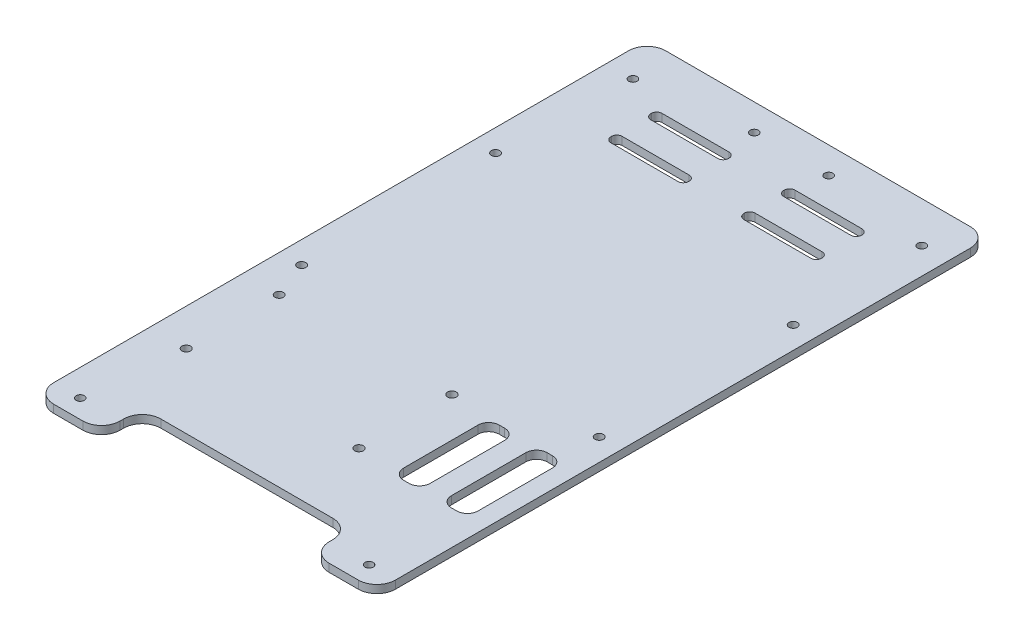
SolidWorks part; units mm, degrees
ref_plane "Front Plane" through (0, 0, 0) normal (0, 0, 1) x (1, 0, 0)
ref_plane "Top Plane" through (0, 0, 0) normal (0, 1, 0) x (1, 0, 0)
ref_plane "Right Plane" through (0, 0, 0) normal (1, 0, 0) x (0, 0, -1)
sketch "Sketch1" plane through (0, 0, 0) normal (0, 1, 0) x (1, 0, 0)
  line L1 (-90, 120) -> (90, 120)
  line L2 (-90, 120) -> (-90, -120)
  line L3 (-90, -120) -> (90, -120)
  line L4 (90, 120) -> (90, -120)
  line L5 (-90, 120) -> (90, -120) construction
  line L6 (-90, -120) -> (90, 120) construction
  point P0 (0, 0)
  dimension "D1" = 180
  dimension "D2" = 240
extrude "Boss-Extrude1" add sketch "Sketch1" along normal blind 3
sketch "Sketch3" plane through (0, 3, 0) normal (0, 1, 0) x (1, 0, 0)
  line L0 (0, 117.3388) -> (0, -121.3792) construction
  line L1 (90, 120) -> (-90, 120) construction
  circle A0 centre (14, 110) radius 1.55
  circle A1 centre (-14, 110) radius 1.55
  dimension "D1" = 3.1
  dimension "D2" = 14
  dimension "D3" = 10
extrude "Cut-Extrude2" cut sketch "Sketch3" against normal through all
sketch "Sketch4" plane through (0, 3, 0) normal (0, 1, 0) x (1, 0, 0)
  line L0 (-117.0852, 0) -> (125.1979, 0) construction
  line L1 (0, 106.2976) -> (0, -114.7172) construction
  line L2 (-2.6902, 10.0007) -> (-2.6902, -138.9813) construction
  circle A4 centre (-50.5, -32.2687) radius 1.6
  circle A5 centre (-50.5, -67.2687) radius 1.6
  circle A6 centre (14.5, -32.2687) radius 1.65
  circle A7 centre (14.5, -67.2687) radius 1.65
  dimension "D1" = 3.2
  dimension "D2" = 3.2
extrude "Cut-Extrude3" cut sketch "Sketch4" against normal through all
sketch "Sketch5" plane through (0, 3, 0) normal (0, 1, 0) x (1, 0, 0)
  line L0 (-125.4171, 0) -> (149.9743, 0) construction
  line L1 (0, -118.5902) -> (0, 143.2176) construction
  circle A0 centre (56, 54.6607) radius 1.6
  circle A1 centre (56, -18.3393) radius 1.6
  circle A2 centre (-56, -18.3393) radius 1.6
  circle A3 centre (-56, 54.6607) radius 1.6
  dimension "D1" = 3.2
  dimension "D2" = 3.2
  dimension "D3" = 3.2
  dimension "D4" = 3.2
extrude "Cut-Extrude4" cut sketch "Sketch5" against normal through all
sketch "Sketch6" plane through (0, 3, 0) normal (0, 1, 0) x (1, 0, 0)
  line L0 (-118.4996, 0) -> (129.5595, 0) construction
  line L1 (0, -107.1236) -> (0, 115.5797) construction
  circle A0 centre (-54.3214, -103.342) radius 1.55
  circle A1 centre (54.3786, -103.342) radius 1.55
  circle A2 centre (-54.3214, 104.658) radius 1.55
  circle A3 centre (54.3786, 104.658) radius 1.55
extrude "Cut-Extrude5" cut sketch "Sketch6" against normal through all
sketch "Sketch7" plane through (0, 3, 0) normal (0, 1, 0) x (1, 0, 0)
  line L0 (90, 120) -> (-90, 120) construction
  line L1 (37.63, 79.7011) -> (12.3993, 79.7011)
  line L2 (-37.63, 83.9122) -> (-12.3993, 83.9122)
  line L3 (-90, 120) -> (-64.3214, 120)
  line L4 (-90, 120) -> (-90, -120)
  line L5 (-90, -120) -> (-64.3214, -120)
  line L6 (-64.3214, 120) -> (-64.3214, -120)
  line L7 (-90, 120) -> (-90, -120) construction
  line L8 (-90, -120) -> (90, -120) construction
  line L9 (0, 130.596) -> (0, -150.1626) construction
  line L10 (-39.3214, -120) -> (39.3786, -120)
  line L11 (-39.3214, -120) -> (-39.3214, -95)
  line L12 (-39.3214, -95) -> (39.3786, -95)
  line L13 (39.3786, -120) -> (39.3786, -95)
  line L14 (90, -120) -> (64.3214, -120)
  line L15 (64.3214, 120) -> (64.3214, -120)
  line L16 (90, 120) -> (64.3214, 120)
  line L17 (90, 120) -> (90, -120)
  line L18 (29.3454, -37.3012) -> (29.3454, -65.3012)
  line L19 (51.3454, -33.3012) -> (53.3454, -33.3012)
  line L20 (47.3454, -37.3012) -> (47.3454, -65.3012)
  line L21 (51.3454, -69.3012) -> (53.3454, -69.3012)
  line L22 (57.3454, -37.3012) -> (57.3454, -65.3012)
  line L23 (33.3454, -33.3012) -> (35.3454, -33.3012)
  line L24 (39.3454, -37.3012) -> (39.3454, -65.3012)
  line L25 (33.3454, -69.3012) -> (35.3454, -69.3012)
  line L26 (37.63, 94.7011) -> (12.3993, 94.7011)
  line L27 (-37.63, 98.9122) -> (-12.3993, 98.9122)
  line L28 (-39.63, 96.9122) -> (-39.63, 96.7011)
  line L29 (-37.63, 94.7011) -> (-12.3993, 94.7011)
  line L30 (-10.3993, 96.9122) -> (-10.3993, 96.7011)
  line L31 (-39.63, 98.9122) -> (-10.3993, 94.7011) construction
  line L32 (-39.63, 94.7011) -> (-10.3993, 98.9122) construction
  line L33 (10.3993, 96.9122) -> (10.3993, 96.7011)
  line L34 (37.63, 98.9122) -> (12.3993, 98.9122)
  line L35 (39.63, 96.9122) -> (39.63, 96.7011)
  line L36 (-39.63, 81.9122) -> (-39.63, 81.7011)
  line L37 (-37.63, 79.7011) -> (-12.3993, 79.7011)
  line L38 (-10.3993, 81.9122) -> (-10.3993, 81.7011)
  line L39 (10.3993, 81.9122) -> (10.3993, 81.7011)
  line L40 (37.63, 83.9122) -> (12.3993, 83.9122)
  line L41 (39.63, 81.9122) -> (39.63, 81.7011)
  line L42 (-39.63, 83.9122) -> (-10.3993, 79.7011) construction
  line L43 (-39.63, 79.7011) -> (-10.3993, 83.9122) construction
  circle A0 centre (-54.3214, -103.342) radius 1.55 construction
  circle A1 centre (54.3786, -103.342) radius 1.55 construction
  arc A2 (51.3454, -69.3012) -> (47.3454, -65.3012) centre (51.3454, -65.3012) cw
  arc A3 (53.3454, -69.3012) -> (57.3454, -65.3012) centre (53.3454, -65.3012) ccw
  arc A4 (57.3454, -37.3012) -> (53.3454, -33.3012) centre (53.3454, -37.3012) ccw
  arc A5 (47.3454, -37.3012) -> (51.3454, -33.3012) centre (51.3454, -37.3012) cw
  arc A6 (35.3454, -69.3012) -> (39.3454, -65.3012) centre (35.3454, -65.3012) ccw
  arc A7 (33.3454, -69.3012) -> (29.3454, -65.3012) centre (33.3454, -65.3012) cw
  arc A8 (35.3454, -33.3012) -> (39.3454, -37.3012) centre (35.3454, -37.3012) cw
  arc A9 (29.3454, -37.3012) -> (33.3454, -33.3012) centre (33.3454, -37.3012) cw
  arc A10 (-37.63, 94.7011) -> (-39.63, 96.7011) centre (-37.63, 96.7011) cw
  arc A11 (-37.63, 98.9122) -> (-39.63, 96.9122) centre (-37.63, 96.9122) ccw
  arc A12 (-10.3993, 96.7011) -> (-12.3993, 94.7011) centre (-12.3993, 96.7011) cw
  arc A13 (-12.3993, 98.9122) -> (-10.3993, 96.9122) centre (-12.3993, 96.9122) cw
  arc A14 (10.3993, 96.7011) -> (12.3993, 94.7011) centre (12.3993, 96.7011) ccw
  arc A15 (12.3993, 98.9122) -> (10.3993, 96.9122) centre (12.3993, 96.9122) ccw
  arc A16 (37.63, 94.7011) -> (39.63, 96.7011) centre (37.63, 96.7011) ccw
  arc A17 (37.63, 98.9122) -> (39.63, 96.9122) centre (37.63, 96.9122) cw
  arc A18 (-37.63, 79.7011) -> (-39.63, 81.7011) centre (-37.63, 81.7011) cw
  arc A19 (-37.63, 83.9122) -> (-39.63, 81.9122) centre (-37.63, 81.9122) ccw
  arc A20 (-10.3993, 81.7011) -> (-12.3993, 79.7011) centre (-12.3993, 81.7011) cw
  arc A21 (-12.3993, 83.9122) -> (-10.3993, 81.9122) centre (-12.3993, 81.9122) cw
  arc A22 (10.3993, 81.7011) -> (12.3993, 79.7011) centre (12.3993, 81.7011) ccw
  arc A23 (12.3993, 83.9122) -> (10.3993, 81.9122) centre (12.3993, 81.9122) ccw
  arc A24 (37.63, 79.7011) -> (39.63, 81.7011) centre (37.63, 81.7011) ccw
  arc A25 (37.63, 83.9122) -> (39.63, 81.9122) centre (37.63, 81.9122) cw
  point P37 (57.3454, -69.3012)
  point P40 (57.3454, -33.3012)
  point P43 (47.3454, -33.3012)
  point P52 (-25.0146, 96.8066)
  point P82 (-25.0146, 81.8066)
  dimension "D1" = 10
  dimension "D8" = 4
  dimension "D9" = 2
  dimension "D2" = 15
  dimension "D3" = 15
  dimension "D4" = 25
  dimension "D5" = 10
  dimension "D6" = 36
  dimension "D7" = 2
  dimension "D10" = 2
extrude "Cut-Extrude6" cut sketch "Sketch7" against normal through all
sketch "Sketch8" plane through (0, 3, 0) normal (0, 1, 0) x (1, 0, 0)
  line L0 (64.3214, 120) -> (64.3214, -120) construction
  line L1 (-64.3214, -120) -> (64.3214, -120)
  line L2 (-64.3214, -120) -> (-64.3214, -110.342)
  line L3 (-64.3214, -110.342) -> (64.3214, -110.342)
  line L4 (64.3214, -120) -> (64.3214, -110.342)
  circle A0 centre (54.3786, -103.342) radius 1.55 construction
  dimension "D1" = 7
extrude "Cut-Extrude7" cut sketch "Sketch8" against normal through all
fillet "Fillet1" radius 7 8 edges at (-64.3214, 1.5, 110.342) (-39.3214, 1.5, 110.342) (39.3786, 1.5, 95) (-39.3214, 1.5, 95) (39.3786, 1.5, 110.342) (64.3214, 1.5, 110.342) (64.3214, 1.5, -120) (-64.3214, 1.5, -120)
